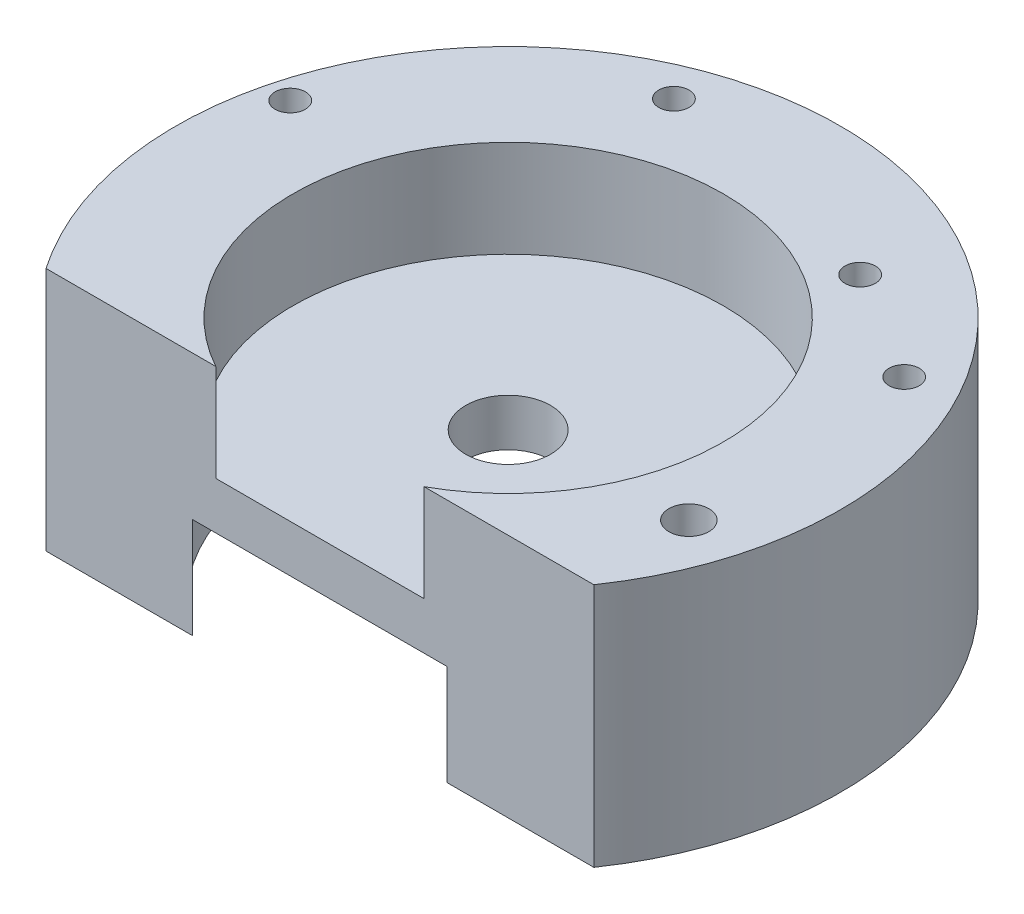
SolidWorks part; units mm, degrees
material "1060 Сплав"
ref_plane "Front Plane" through (0, 0, 0) normal (0, 0, 1) x (1, 0, 0)
ref_plane "Top Plane" through (0, 0, 0) normal (0, 1, 0) x (1, 0, 0)
ref_plane "Right Plane" through (0, 0, 0) normal (1, 0, 0) x (0, 0, -1)
sketch "Эскиз1" plane through (0, 0, 0) normal (0, 0, 1) x (1, 0, 0)
  line L0 (0, 0) -> (0, 19.6284) construction
  line L1 (-27.425, 0) -> (-18.75, 0)
  line L2 (-18.75, 0) -> (-18.75, 8.3)
  line L3 (-18.75, 8.3) -> (-3.5, 8.3)
  line L4 (-3.5, 8.3) -> (-3.5, 12.2)
  line L5 (-3.5, 12.2) -> (-17.75, 12.2)
  line L6 (-17.75, 12.2) -> (-17.75, 20.2)
  line L7 (-17.75, 20.2) -> (-27.425, 20.2)
  line L8 (-27.425, 20.2) -> (-27.425, 0)
  line L9 (-18.75, 0) -> (0, 0) construction
  dimension "D1" = 7
  dimension "D2" = 54.85
  dimension "D3" = 20.2
  dimension "D4" = 8.3
  dimension "D5" = 8
  dimension "D6" = 37.5
  dimension "D7" = 35.5
revolve "Повернуть1" add sketch "Эскиз1" angle 360 about L0
sketch "Эскиз2" plane through (0, 0, 0) normal (0, -1, 0) x (1, 0, 0)
  line L0 (4.9828, -26.9686) -> (27.425, -26.9686) construction
  line L1 (22.6032, 27.425) -> (-22.6032, 27.425)
  line L2 (22.6032, 27.425) -> (22.6032, 15.5314)
  line L3 (22.6032, 15.5314) -> (-22.6032, 15.5314)
  line L4 (-22.6032, 27.425) -> (-22.6032, 15.5314)
  circle A0 centre (0, 0) radius 27.425 construction
  dimension "D1" = 42.5
extrude "Вырез-Вытянуть1" cut sketch "Эскиз2" against normal through all
hole_wizard "M3 Tapped Hole1" positions "Эскиз4" profile "Эскиз5" tap size "M3" standard "ISO"
sketch "Эскиз4" plane through (0, 20.2, 0) normal (0, 1, 0) x (1, 0, 0)
  point P0 (11.4354, 17.6134)
sketch "Эскиз5" plane through (11.4354, 20.2, -17.6134) normal (1, 0, 0) x (0, 0, 1)
  line L0 (0, 0) -> (0, 15.7511)
  line L1 (0, 15.7511) -> (1.25, 15)
  line L2 (1.25, 15) -> (1.25, 0)
  line L5 (1.25, 0) -> (0, 0)
  line L10 (0, 15.7511) -> (-1.25, 15) construction
  line L11 (0, -6.35) -> (0, 107.95) construction
  dimension "Диаметр сверла" = 2.5
  dimension "Глубина сверла" = 15
  dimension "Угол заточки сверла" = 118
cosmetic thread "Отверстие резьбы1" parameters "D1"=5.5, "D2"=3
sketch "Эскиз6" plane through (0, 0, 0) normal (0, -1, 0) x (1, 0, 0)
  line L0 (8.5928, 15.5314) -> (22.6032, 15.5314) construction
  line B0 (0, 0) -> (5.4157, -16.9561)
  line B1 (5.4157, -16.9561) -> (20.5619, -12.1186)
  line B2 (5.4157, -16.9561) -> (5.7047, -17.8611)
  line B3 (5.7047, -17.8611) -> (-8.8223, -22.5009)
  line B4 (0, 0) -> (-0.3742, 1.1717)
  line B5 (-0.3742, 1.1717) -> (-24.5224, -6.5411)
  circle B6 centre (0, 0) radius 27.25
  circle B7 centre (20.5619, -12.1186) radius 1.25
  circle B8 centre (-8.8223, -22.5009) radius 1.25
  circle B9 centre (-24.5224, -6.5411) radius 1.25
  circle B10 centre (0, 0) radius 1.55
  dimension "D1" = 27.65
sketch_block_instance "Блок3-1"
sketch_block "Блок3" parameters "D7"=54.5, "D8"=2.5, "D9"=3.1, "D1"=15.9, "D2"=15.25, "D3"=18.75, "D4"=17.8, "D5"=1.23, "D6"=25.35
extrude "Вырез-Вытянуть3" cut sketch "Эскиз6" along normal blind 10 from surface at -20.2 starting at face at (11.4354, 20.2, -16.3634)
hole_wizard "M4x0.7 Tapped Hole1" positions "Sketch1" profile "Sketch2" tap size "M4x0.7" standard "ANSI Metric" end condition through all
sketch "Sketch1" plane through (0, 0, 0) normal (0, -1, 0) x (-1, 0, 0)
  point P0 (-21.9096, -6.9978)
sketch "Sketch2" plane through (21.9096, 0, 6.9978) normal (1, 0, 0) x (0, 0, -1)
  line L0 (0, 0) -> (0, 20.2)
  line L1 (0, 20.2) -> (1.65, 20.2)
  line L2 (1.65, 20.2) -> (1.65, 0)
  line L5 (1.65, 0) -> (0, 0)
  line L11 (0, -6.35) -> (0, 107.95) construction
  dimension "Thru Tap Drill Dia." = 3.3
  dimension "Thru Tap Drill Depth" = 20.2
cosmetic thread "Hole Thread1" parameters "D2"=4
